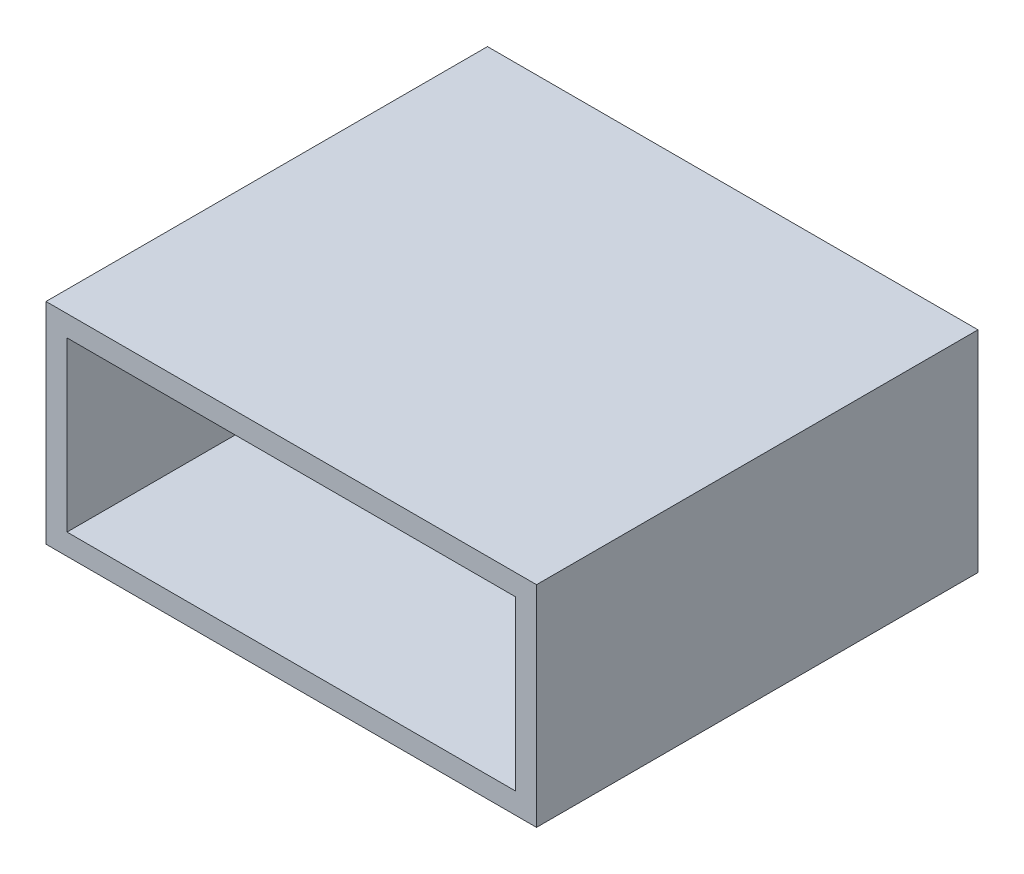
SolidWorks part; units mm, degrees
ref_plane "Front Plane" through (0, 0, 0) normal (0, 0, 1) x (1, 0, 0)
ref_plane "Top Plane" through (0, 0, 0) normal (0, 1, 0) x (1, 0, 0)
ref_plane "Right Plane" through (0, 0, 0) normal (1, 0, 0) x (0, 0, -1)
sketch "Sketch1" plane through (0, 0, 0) normal (0, 0, 1) x (1, 0, 0)
  line L0 (-32, -12) -> (-32, 12)
  line L1 (-35, -15) -> (35, -15)
  line L2 (-35, -15) -> (-35, 15)
  line L3 (-35, 15) -> (35, 15)
  line L4 (35, -15) -> (35, 15)
  line L5 (-35, -15) -> (35, 15) construction
  line L6 (-35, 15) -> (35, -15) construction
  line L7 (-32, 12) -> (32, 12)
  line L8 (32, -12) -> (32, 12)
  line L9 (-32, -12) -> (32, -12)
  point P0 (0, 0)
  dimension "D1" = 30
  dimension "D2" = 70
  dimension "D3" = 3
extrude "Boss-Extrude1" add sketch "Sketch1" along normal blind 60
sketch "Sketch2" plane through (0, 0, 0) normal (0, 0, -1) x (-1, 0, 0)
  line L8 (-35, 15) -> (-35, -15)
  line L9 (-35, -15) -> (35, -15)
  line L10 (35, -15) -> (35, 15)
  line L11 (35, 15) -> (-35, 15)
  line L12 (-35, 15) -> (-35, -15)
  line L13 (-35, -15) -> (35, -15)
  line L14 (35, -15) -> (35, 15)
  line L15 (35, 15) -> (-35, 15)
  dimension "D1" = 0
extrude "Boss-Extrude2" add sketch "Sketch2" along normal blind 3
